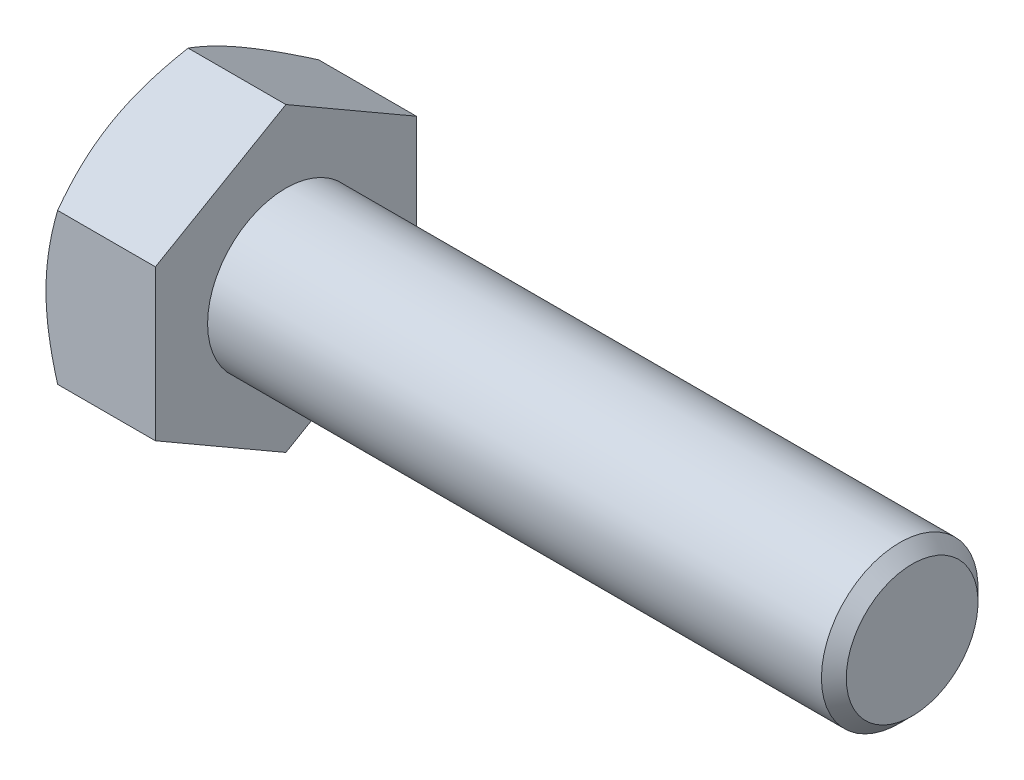
SolidWorks part; units mm, degrees
extrude "BaseHead" add sketch "Sketch1" along normal blind 13.3096
sketch "Sketch1" plane through (0, 0, 0) normal (1, 0, 0) x (0, 0, -1)
  line L0 (15.875, 9.1654) -> (15.875, -9.1654)
  line L1 (-15.875, 9.1654) -> (-15.875, -9.1654)
  line L2 (15.875, -9.1654) -> (0, -18.3309)
  line L3 (0, -18.3309) -> (-15.875, -9.1654)
  line L4 (15.875, 9.1654) -> (0, 18.3309)
  line L5 (0, 18.3309) -> (-15.875, 9.1654)
  dimension "Width_flats" = 31.75
  dimension "D2" = 120
  dimension "D3" = 15.875
  dimension "D4" = 15.875
  dimension "D5" = 15.875
ref_plane "Plane1" through (0, 0, 0) normal (0, 0, 1) x (1, 0, 0)
ref_plane "Plane2" through (0, 0, 0) normal (0, 1, 0) x (1, 0, 0)
ref_plane "Plane3" through (0, 0, 0) normal (1, 0, 0) x (0, 0, -1)
other "Configuration Table"
sketch "BodySke" plane through (0, 0, 0) normal (0, 0, 1) x (1, 0, 0)
  line L0 (0, 9.1654) -> (0, -9.1654) construction
  line L1 (0, 0) -> (89.5096, 0)
  line L2 (0, 0) -> (0, 9.525)
  line L3 (0, 9.525) -> (87.997, 9.525)
  line L4 (89.5096, 0) -> (89.5096, 8.0124)
  line L5 (13.3096, 18.3309) -> (13.3096, 9.1654) construction
  line L6 (89.5096, 8.0124) -> (87.997, 9.525)
  line L7 (0, 0) -> (96.52, 0) construction
  line L8 (89.5096, -8.0124) -> (87.997, -9.525) construction
  line L9 (0, -9.525) -> (87.997, -9.525) construction
  line L10 (15.8496, 15.24) -> (15.8496, -3.81) construction
  line L11 (13.3096, 15.24) -> (13.3096, -3.81) construction
  line L12 (13.3096, 9.1654) -> (13.3096, -9.1654) construction
  dimension "Diameter" = 19.05
revolve "BaseBody" add sketch "BodySke" angle 360 about L7
cosmetic thread "ThreadCosmetic" [suppressed] parameters "Thread_length"=73.66, "Thread_minor"=16.0249
sketch "Sketch3" plane through (0, 0, 0) normal (0, 0, 1) x (1, 0, 0)
  line L0 (0, 15.875) -> (5.0841, 24.6809)
  line L1 (0, 18.3309) -> (0, 9.1654) construction
  line L2 (5.0841, 24.6809) -> (5.0841, 31.0309)
  line L3 (5.0841, 31.0309) -> (-12.7, 31.0309)
  line L4 (-12.7, 31.0309) -> (-12.7, 15.875)
  line L5 (-12.7, 15.875) -> (0, 15.875)
  line L6 (0, 0) -> (99.06, 0) construction
  line L7 (13.3096, 18.3309) -> (0, 18.3309) construction
  dimension "D1" = 15.875
  dimension "D2" = 6.35
  dimension "D3" = 12.7
  dimension "D4" = 6.35
  dimension "Head_ch_ang" = 30
revolve "HeadChamfer" cut sketch "Sketch3" angle 360 about L6
fillet "HeadFillet" [suppressed] radius 1.524
sketch "ThdSchSke" plane through (0, 0, 0) normal (0, 0, 1) x (1, 0, 0)
  line L0 (15.8496, -8.0124) -> (14.7905, -9.525)
  line L1 (15.8496, -8.0124) -> (16.9087, -9.525)
  line L2 (16.9087, -9.525) -> (16.9087, -11.9062)
  line L3 (-3.175, 0) -> (5.1513, 0) construction
  line L5 (16.9087, -11.9062) -> (14.7905, -11.9062)
  line L6 (14.7905, -11.9062) -> (14.7905, -9.525)
  dimension "Thread_minor" = 16.0249
  dimension "Diameter" = 19.05
  dimension "Start" = 15.8496
revolve "ThreadSchematic" [suppressed] cut sketch "ThdSchSke" angle 360 about L3
pattern_linear "ThdSchPat" [suppressed]
equation "\"D3@Sketch1\" = \"Width_flats@Sketch1\" / 2"
equation "\"D4@Sketch1\" = \"D3@Sketch1\""
equation "\"D5@Sketch1\" = \"D4@Sketch1\""
equation "\"Thread_minor@ThreadCosmetic\" = \"Minor_dia@BodySke\""
equation "\"D1@Sketch3\" = \"Width_flats@Sketch1\" / 2"
equation "\"Thread_length@ThreadCosmetic\" = ((sgn( (\"Length@BodySke\" - \"Advance@BodySke\" ) - \"Thread_nom@BodySke\" )-1)*( (\"Length@BodySke\" - \"Advance@BodySke\" ) - \"Thread_nom@BodySke\" ))/-2+ \"Thread_nom@BodySke\""
equation "\"Thread_minor@ThdSchSke\" = \"Minor_dia@BodySke\""
equation "\"Diameter@ThdSchSke\" = \"Diameter@BodySke\""
equation "\"Overcut@ThdSchSke\" = \"Diameter@BodySke\" * 1.25"
equation "\"Start@ThdSchSke\" = \"Head_ht@BaseHead\" + \"Length@BodySke\" - \"Thread_length@ThreadCosmetic\"  '---Non-countersunk---"
equation "\"Num_threads@ThdSchPat\" = int( \"Thread_length@ThreadCosmetic\" / \"Advance@BodySke\" + 0.999 )  + 1"
equation "\"Advance@ThdSchPat\" = \"Thread_length@ThreadCosmetic\" /  (\"Num_threads@ThdSchPat\" - 1) 'relax it"
equation "\"Num_threads@ThdSchPat\" = \"Num_threads@ThdSchPat\" - sgn( \"Num_threads@ThdSchPat\" - 1) '---chamfered tips only---"
